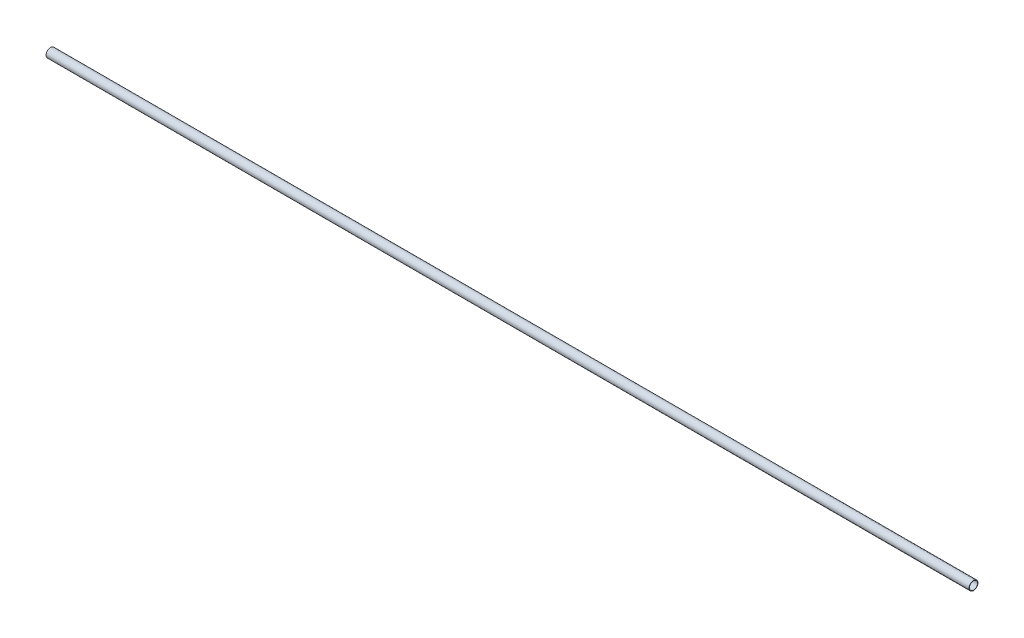
SolidWorks part; units mm, degrees
material "Galvanized Steel"
ref_plane "Front Plane" through (0, 0, 0) normal (0, 0, 1) x (1, 0, 0)
ref_plane "Top Plane" through (0, 0, 0) normal (0, 1, 0) x (1, 0, 0)
ref_plane "Right Plane" through (0, 0, 0) normal (1, 0, 0) x (0, 0, -1)
sketch "Sketch3" plane through (0, 0, 0) normal (1, 0, 0) x (0, 0, -1)
  circle A0 centre (0, 0) radius 13.3223
  circle A1 centre (0, 0) radius 14.7701
  dimension "D1" = 26.6446
  dimension "D2" = 29.5402
extrude "Boss-Extrude1" add sketch "Sketch3" along normal blind 3048
